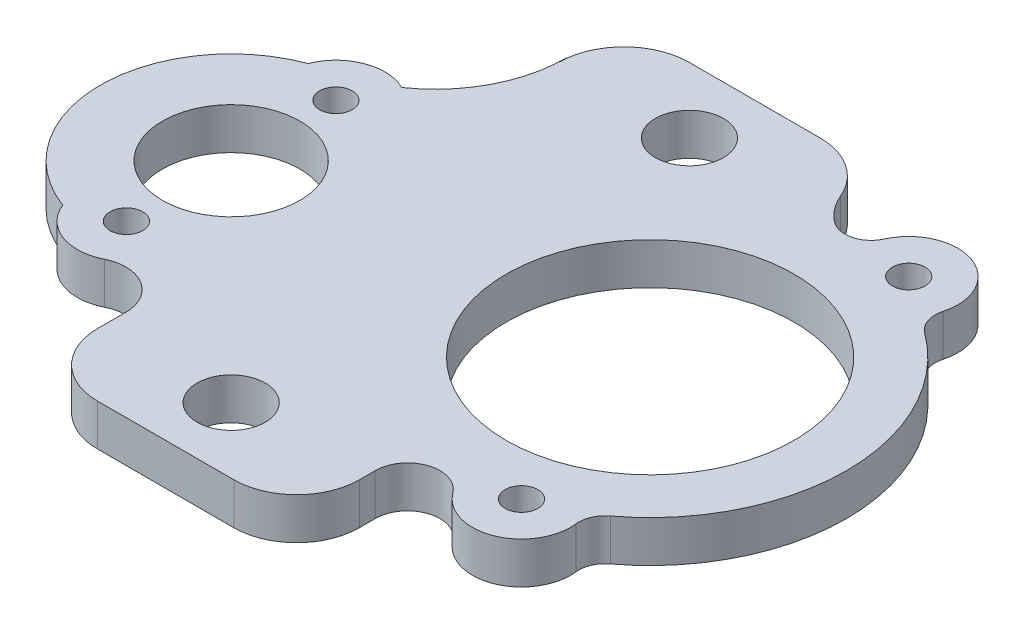
SolidWorks part; units mm, degrees
ref_plane "Front Plane" through (0, 0, 0) normal (0, 0, 1) x (1, 0, 0)
ref_plane "Top Plane" through (0, 0, 0) normal (0, 1, 0) x (1, 0, 0)
ref_plane "Right Plane" through (0, 0, 0) normal (1, 0, 0) x (0, 0, -1)
ref_plane "Plane1" through (0, 73.175, 0) normal (0, 1, 0) x (1, 0, 0)
sketch "Sketch1" plane through (0, 73.175, 0) normal (0, 1, 0) x (1, 0, 0)
  line L0 (15, -131.0431) -> (-1.022, -131.0431)
  line L1 (0, -169.0663) -> (0, -171.2431)
  line L2 (4.8, -176.0431) -> (15.2, -176.0431)
  line L3 (20, -171.2431) -> (20, -170.0645)
  arc A0 (-1.022, -131.0431) -> (-4.3309, -143.685) centre (-10, -135.4472) cw
  arc A1 (-4.3309, -143.685) -> (-9.4904, -145.672) centre (-6, -147.0431) ccw
  arc A2 (-9.4904, -145.672) -> (-9.4904, -164.4142) centre (-6, -155.0431) ccw
  arc A3 (-9.4904, -164.4142) -> (-4.3309, -166.4012) centre (-6, -163.0431) ccw
  arc A4 (-4.3309, -166.4012) -> (0, -169.0663) centre (-2.997, -169.0851) cw
  arc A5 (0, -171.2431) -> (4.8, -176.0431) centre (4.8, -171.2431) ccw
  arc A6 (15.2, -176.0431) -> (20, -171.2431) centre (15.2, -171.2431) ccw
  arc A7 (20, -170.0645) -> (24.4525, -168.5648) centre (22.469, -170.0352) cw
  arc A8 (24.4525, -168.5648) -> (31.1895, -165.8944) centre (27.4651, -166.3316) ccw
  arc A9 (31.1895, -165.8944) -> (31.9787, -164.0591) centre (33.1759, -165.6612) cw
  arc A10 (31.9787, -164.0591) -> (31.8926, -139.9633) centre (23, -152.0431) ccw
  arc A11 (31.8926, -139.9633) -> (31.1498, -137.8223) centre (33.0783, -138.3527) cw
  arc A12 (31.1498, -137.8223) -> (24.1177, -135.2817) centre (27.5341, -136.8279) ccw
  arc A13 (24.1177, -135.2817) -> (21.0462, -136.0188) centre (22.2956, -134.4571) cw
  arc A14 (21.0462, -136.0188) -> (19.6147, -134.1184) centre (24.0448, -132.2707) cw
  arc A15 (19.6147, -134.1184) -> (15, -131.0431) centre (15, -136.0431) ccw
extrude "Boss-Extrude1" add sketch "Sketch1" against normal blind 3.175
sketch "Sketch2" plane through (0, 70, 0) normal (0, -1, 0) x (1, 0, 0)
  line L0 (0, 136.0431) -> (0, 135.4472)
  line L1 (-1.022, 131.0431) -> (5, 131.0431)
  arc A0 (5, 131.0431) -> (0, 136.0431) centre (5, 136.0431) cw
  arc A1 (0, 135.4472) -> (-1.022, 131.0431) centre (-10, 135.4472) cw
extrude "Cut-Extrude1" cut sketch "Sketch2" against normal blind 3.175
hole_wizard "Ø2.5 (2.5) Diameter Hole1" positions "Sketch4" profile "Sketch3" hole size "Ø2.5" standard "ANSI Metric"
sketch "Sketch4" plane through (0, 73.175, 0) normal (0, 1, 0) x (1, 0, 0)
  point P0 (27.5341, -136.8279)
  point P1 (27.4651, -166.3316)
  point P2 (-6, -147.0431)
  point P3 (-6, -163.0431)
sketch "Sketch3" plane through (27.5341, 73.175, 136.8279) normal (1, 0, 0) x (0, 0, 1)
  line L0 (0, 0) -> (0, 3.175)
  line L1 (0, 3.175) -> (1.25, 3.175)
  line L2 (1.25, 3.175) -> (1.25, 0)
  line L5 (1.25, 0) -> (0, 0)
  line L11 (0, -6.35) -> (0, 107.95) construction
  dimension "Thru Hole Dia." = 2.5
  dimension "Thru Hole Depth" = 3.175
hole_wizard "Ø22.0 (22) Diameter Hole1" positions "Sketch6" profile "Sketch5" hole size "Ø22.0" standard "ANSI Metric"
sketch "Sketch6" plane through (0, 73.175, 0) normal (0, 1, 0) x (1, 0, 0)
  point P0 (23, -152.0431)
sketch "Sketch5" plane through (23, 73.175, 152.0431) normal (1, 0, 0) x (0, 0, 1)
  line L0 (0, 0) -> (0, 3.175)
  line L1 (0, 3.175) -> (11, 3.175)
  line L2 (11, 3.175) -> (11, 0)
  line L5 (11, 0) -> (0, 0)
  line L11 (0, -6.35) -> (0, 107.95) construction
  dimension "Thru Hole Dia." = 22
  dimension "Thru Hole Depth" = 3.175
hole_wizard "Ø10.5 (10.5) Diameter Hole1" positions "Sketch8" profile "Sketch7" hole size "Ø10.5" standard "ANSI Metric"
sketch "Sketch8" plane through (0, 73.175, 0) normal (0, 1, 0) x (1, 0, 0)
  point P0 (-6, -155.0431)
sketch "Sketch7" plane through (-6, 73.175, 155.0431) normal (1, 0, 0) x (0, 0, 1)
  line L0 (0, 0) -> (0, 3.175)
  line L1 (0, 3.175) -> (5.25, 3.175)
  line L2 (5.25, 3.175) -> (5.25, 0)
  line L5 (5.25, 0) -> (0, 0)
  line L11 (0, -6.35) -> (0, 107.95) construction
  dimension "Thru Hole Dia." = 10.5
  dimension "Thru Hole Depth" = 3.175
hole_wizard "Ø5.2 (5.2) Diameter Hole1" positions "Sketch10" profile "Sketch9" hole size "Ø5.2" standard "ANSI Metric"
sketch "Sketch10" plane through (0, 73.175, 0) normal (0, 1, 0) x (1, 0, 0)
  point P0 (10, -171.0431)
  point P1 (10, -136.0431)
sketch "Sketch9" plane through (10, 73.175, 171.0431) normal (1, 0, 0) x (0, 0, 1)
  line L0 (0, 0) -> (0, 3.175)
  line L1 (0, 3.175) -> (2.6, 3.175)
  line L2 (2.6, 3.175) -> (2.6, 0)
  line L5 (2.6, 0) -> (0, 0)
  line L11 (0, -6.35) -> (0, 107.95) construction
  dimension "Thru Hole Dia." = 5.2
  dimension "Thru Hole Depth" = 3.175
